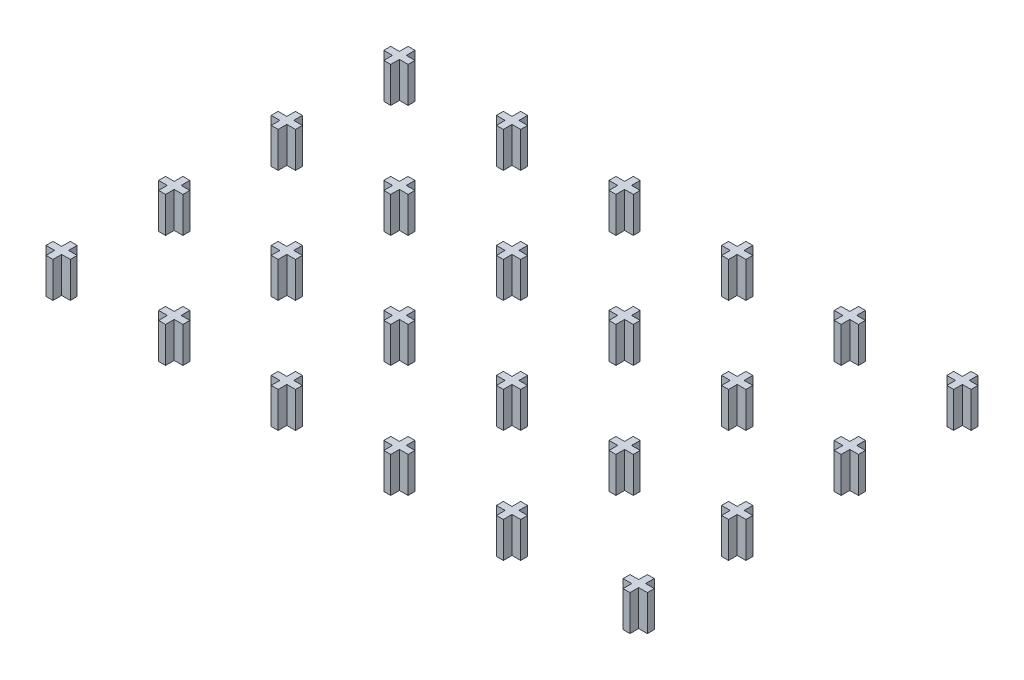
SolidWorks part; units mm, degrees
ref_plane "Front Plane" through (0, 0, 0) normal (0, 0, 1) x (1, 0, 0)
ref_plane "Top Plane" through (0, 0, 0) normal (0, 1, 0) x (1, 0, 0)
ref_plane "Right Plane" through (0, 0, 0) normal (1, 0, 0) x (0, 0, -1)
sketch "Sketch1" plane through (0, 0, 0) normal (0, 1, 0) x (1, 0, 0)
  line L0 (-32.7876, 10.5773) -> (-51.7876, 10.5773) construction
  line L1 (-51.7876, 10.5773) -> (-70.7876, 10.5773) construction
  line L2 (-51.7876, 10.5773) -> (-51.7876, 29.5773) construction
  line L3 (-51.7876, 29.5773) -> (-70.7876, 29.5773) construction
  line L4 (-70.7876, 10.5773) -> (-70.7876, 29.5773) construction
  line L5 (-51.7876, 10.5773) -> (-70.7876, 29.5773) construction
  line L6 (-51.7876, 29.5773) -> (-70.7876, 10.5773) construction
  line L7 (-32.7876, 10.5773) -> (-32.7876, 29.5773) construction
  line L8 (-32.7876, 29.5773) -> (-51.7876, 29.5773) construction
  line L9 (-51.7876, 10.5773) -> (-51.7876, 29.5773) construction
  line L10 (-32.7876, 10.5773) -> (-51.7876, 29.5773) construction
  line L11 (-32.7876, 29.5773) -> (-51.7876, 10.5773) construction
  line L12 (-13.7876, 10.5773) -> (-32.7876, 10.5773) construction
  line L13 (-13.7876, 10.5773) -> (-13.7876, 29.5773) construction
  line L14 (-13.7876, 29.5773) -> (-32.7876, 29.5773) construction
  line L15 (-32.7876, 10.5773) -> (-32.7876, 29.5773) construction
  line L16 (-13.7876, 10.5773) -> (-32.7876, 29.5773) construction
  line L17 (-13.7876, 29.5773) -> (-32.7876, 10.5773) construction
  line L18 (-32.7876, -8.4227) -> (-51.7876, -8.4227) construction
  line L19 (-51.7876, -8.4227) -> (-70.7876, -8.4227) construction
  line L20 (-51.7876, -8.4227) -> (-51.7876, 10.5773) construction
  line L21 (-51.7876, 10.5773) -> (-70.7876, 10.5773) construction
  line L22 (-70.7876, -8.4227) -> (-70.7876, 10.5773) construction
  line L23 (-51.7876, -8.4227) -> (-70.7876, 10.5773) construction
  line L24 (-51.7876, 10.5773) -> (-70.7876, -8.4227) construction
  line L25 (-32.7876, -8.4227) -> (-32.7876, 10.5773) construction
  line L26 (-32.7876, 10.5773) -> (-51.7876, 10.5773) construction
  line L27 (-51.7876, -8.4227) -> (-51.7876, 10.5773) construction
  line L28 (-32.7876, -8.4227) -> (-51.7876, 10.5773) construction
  line L29 (-32.7876, 10.5773) -> (-51.7876, -8.4227) construction
  line L30 (-13.7876, -8.4227) -> (-32.7876, -8.4227) construction
  line L31 (-13.7876, -8.4227) -> (-13.7876, 10.5773) construction
  line L32 (-13.7876, 10.5773) -> (-32.7876, 10.5773) construction
  line L33 (-32.7876, -8.4227) -> (-32.7876, 10.5773) construction
  line L34 (-13.7876, -8.4227) -> (-32.7876, 10.5773) construction
  line L35 (-13.7876, 10.5773) -> (-32.7876, -8.4227) construction
  line L36 (-32.7876, -27.4227) -> (-51.7876, -27.4227) construction
  line L37 (-51.7876, -27.4227) -> (-70.7876, -27.4227) construction
  line L38 (-51.7876, -27.4227) -> (-51.7876, -8.4227) construction
  line L39 (-51.7876, -8.4227) -> (-70.7876, -8.4227) construction
  line L40 (-70.7876, -27.4227) -> (-70.7876, -8.4227) construction
  line L41 (-51.7876, -27.4227) -> (-70.7876, -8.4227) construction
  line L42 (-51.7876, -8.4227) -> (-70.7876, -27.4227) construction
  line L43 (-32.7876, -27.4227) -> (-32.7876, -8.4227) construction
  line L44 (-32.7876, -8.4227) -> (-51.7876, -8.4227) construction
  line L45 (-51.7876, -27.4227) -> (-51.7876, -8.4227) construction
  line L46 (-32.7876, -27.4227) -> (-51.7876, -8.4227) construction
  line L47 (-32.7876, -8.4227) -> (-51.7876, -27.4227) construction
  line L48 (-13.7876, -27.4227) -> (-32.7876, -27.4227) construction
  line L49 (-13.7876, -27.4227) -> (-13.7876, -8.4227) construction
  line L50 (-13.7876, -8.4227) -> (-32.7876, -8.4227) construction
  line L51 (-32.7876, -27.4227) -> (-32.7876, -8.4227) construction
  line L52 (-13.7876, -27.4227) -> (-32.7876, -8.4227) construction
  line L53 (-13.7876, -8.4227) -> (-32.7876, -27.4227) construction
  line L54 (24.2124, 10.5773) -> (5.2124, 10.5773) construction
  line L55 (5.2124, 10.5773) -> (-13.7876, 10.5773) construction
  line L56 (5.2124, 10.5773) -> (5.2124, 29.5773) construction
  line L57 (5.2124, 29.5773) -> (-13.7876, 29.5773) construction
  line L58 (-13.7876, 10.5773) -> (-13.7876, 29.5773) construction
  line L59 (5.2124, 10.5773) -> (-13.7876, 29.5773) construction
  line L60 (5.2124, 29.5773) -> (-13.7876, 10.5773) construction
  line L61 (24.2124, 10.5773) -> (24.2124, 29.5773) construction
  line L62 (24.2124, 29.5773) -> (5.2124, 29.5773) construction
  line L63 (5.2124, 10.5773) -> (5.2124, 29.5773) construction
  line L64 (24.2124, 10.5773) -> (5.2124, 29.5773) construction
  line L65 (24.2124, 29.5773) -> (5.2124, 10.5773) construction
  line L66 (43.2124, 10.5773) -> (24.2124, 10.5773) construction
  line L67 (43.2124, 10.5773) -> (43.2124, 29.5773) construction
  line L68 (43.2124, 29.5773) -> (24.2124, 29.5773) construction
  line L69 (24.2124, 10.5773) -> (24.2124, 29.5773) construction
  line L70 (43.2124, 10.5773) -> (24.2124, 29.5773) construction
  line L71 (43.2124, 29.5773) -> (24.2124, 10.5773) construction
  line L72 (24.2124, -8.4227) -> (5.2124, -8.4227) construction
  line L73 (5.2124, -8.4227) -> (-13.7876, -8.4227) construction
  line L74 (5.2124, -8.4227) -> (5.2124, 10.5773) construction
  line L75 (5.2124, 10.5773) -> (-13.7876, 10.5773) construction
  line L76 (-13.7876, -8.4227) -> (-13.7876, 10.5773) construction
  line L77 (5.2124, -8.4227) -> (-13.7876, 10.5773) construction
  line L78 (5.2124, 10.5773) -> (-13.7876, -8.4227) construction
  line L79 (24.2124, -8.4227) -> (24.2124, 10.5773) construction
  line L80 (24.2124, 10.5773) -> (5.2124, 10.5773) construction
  line L81 (5.2124, -8.4227) -> (5.2124, 10.5773) construction
  line L82 (24.2124, -8.4227) -> (5.2124, 10.5773) construction
  line L83 (24.2124, 10.5773) -> (5.2124, -8.4227) construction
  line L84 (43.2124, -8.4227) -> (24.2124, -8.4227) construction
  line L85 (43.2124, -8.4227) -> (43.2124, 10.5773) construction
  line L86 (43.2124, 10.5773) -> (24.2124, 10.5773) construction
  line L87 (24.2124, -8.4227) -> (24.2124, 10.5773) construction
  line L88 (43.2124, -8.4227) -> (24.2124, 10.5773) construction
  line L89 (43.2124, 10.5773) -> (24.2124, -8.4227) construction
  line L90 (24.2124, -27.4227) -> (5.2124, -27.4227) construction
  line L91 (5.2124, -27.4227) -> (-13.7876, -27.4227) construction
  line L92 (5.2124, -27.4227) -> (5.2124, -8.4227) construction
  line L93 (5.2124, -8.4227) -> (-13.7876, -8.4227) construction
  line L94 (-13.7876, -27.4227) -> (-13.7876, -8.4227) construction
  line L95 (5.2124, -27.4227) -> (-13.7876, -8.4227) construction
  line L96 (5.2124, -8.4227) -> (-13.7876, -27.4227) construction
  line L97 (24.2124, -27.4227) -> (24.2124, -8.4227) construction
  line L98 (24.2124, -8.4227) -> (5.2124, -8.4227) construction
  line L99 (5.2124, -27.4227) -> (5.2124, -8.4227) construction
  line L100 (24.2124, -27.4227) -> (5.2124, -8.4227) construction
  line L101 (24.2124, -8.4227) -> (5.2124, -27.4227) construction
  line L102 (43.2124, -27.4227) -> (24.2124, -27.4227) construction
  line L103 (43.2124, -27.4227) -> (43.2124, -8.4227) construction
  line L104 (43.2124, -8.4227) -> (24.2124, -8.4227) construction
  line L105 (24.2124, -27.4227) -> (24.2124, -8.4227) construction
  line L106 (43.2124, -27.4227) -> (24.2124, -8.4227) construction
  line L107 (43.2124, -8.4227) -> (24.2124, -27.4227) construction
  line L108 (-61.8726, 22.1273) -> (-60.7026, 22.1273)
  line L109 (-60.7026, 22.1273) -> (-60.7026, 20.6623)
  line L110 (-60.7026, 20.6623) -> (-59.2376, 20.6623)
  line L111 (-59.2376, 20.6623) -> (-59.2376, 19.4923)
  line L112 (-59.2376, 19.4923) -> (-60.7026, 19.4923)
  line L113 (-60.7026, 19.4923) -> (-60.7026, 18.0273)
  line L114 (-60.7026, 18.0273) -> (-61.8726, 18.0273)
  line L115 (-61.8726, 18.0273) -> (-61.8726, 19.4923)
  line L116 (-61.8726, 19.4923) -> (-63.3376, 19.4923)
  line L117 (-63.3376, 19.4923) -> (-63.3376, 20.6623)
  line L118 (-63.3376, 20.6623) -> (-61.8726, 20.6623)
  line L119 (-61.8726, 20.6623) -> (-61.8726, 22.1273)
  line L120 (-61.8726, 20.6623) -> (-60.7026, 19.4923) construction
  line L121 (-61.8726, 19.4923) -> (-60.7026, 20.6623) construction
  line L122 (-61.8726, 3.1273) -> (-60.7026, 3.1273)
  line L123 (-60.7026, 3.1273) -> (-60.7026, 1.6623)
  line L124 (-60.7026, 1.6623) -> (-59.2376, 1.6623)
  line L125 (-59.2376, 1.6623) -> (-59.2376, 0.4923)
  line L126 (-59.2376, 0.4923) -> (-60.7026, 0.4923)
  line L127 (-60.7026, 0.4923) -> (-60.7026, -0.9727)
  line L128 (-60.7026, -0.9727) -> (-61.8726, -0.9727)
  line L129 (-61.8726, -0.9727) -> (-61.8726, 0.4923)
  line L130 (-61.8726, 0.4923) -> (-63.3376, 0.4923)
  line L131 (-63.3376, 0.4923) -> (-63.3376, 1.6623)
  line L132 (-63.3376, 1.6623) -> (-61.8726, 1.6623)
  line L133 (-61.8726, 1.6623) -> (-61.8726, 3.1273)
  line L134 (-61.8726, 1.6623) -> (-60.7026, 0.4923) construction
  line L135 (-61.8726, 0.4923) -> (-60.7026, 1.6623) construction
  line L136 (-61.8726, -15.8727) -> (-60.7026, -15.8727)
  line L137 (-60.7026, -15.8727) -> (-60.7026, -17.3377)
  line L138 (-60.7026, -17.3377) -> (-59.2376, -17.3377)
  line L139 (-59.2376, -17.3377) -> (-59.2376, -18.5077)
  line L140 (-59.2376, -18.5077) -> (-60.7026, -18.5077)
  line L141 (-60.7026, -18.5077) -> (-60.7026, -19.9727)
  line L142 (-60.7026, -19.9727) -> (-61.8726, -19.9727)
  line L143 (-61.8726, -19.9727) -> (-61.8726, -18.5077)
  line L144 (-61.8726, -18.5077) -> (-63.3376, -18.5077)
  line L145 (-63.3376, -18.5077) -> (-63.3376, -17.3377)
  line L146 (-63.3376, -17.3377) -> (-61.8726, -17.3377)
  line L147 (-61.8726, -17.3377) -> (-61.8726, -15.8727)
  line L148 (-61.8726, -17.3377) -> (-60.7026, -18.5077) construction
  line L149 (-61.8726, -18.5077) -> (-60.7026, -17.3377) construction
  line L150 (-42.8726, -15.8727) -> (-41.7026, -15.8727)
  line L151 (-41.7026, -15.8727) -> (-41.7026, -17.3377)
  line L152 (-41.7026, -17.3377) -> (-40.2376, -17.3377)
  line L153 (-40.2376, -17.3377) -> (-40.2376, -18.5077)
  line L154 (-40.2376, -18.5077) -> (-41.7026, -18.5077)
  line L155 (-41.7026, -18.5077) -> (-41.7026, -19.9727)
  line L156 (-41.7026, -19.9727) -> (-42.8726, -19.9727)
  line L157 (-42.8726, -19.9727) -> (-42.8726, -18.5077)
  line L158 (-42.8726, -18.5077) -> (-44.3376, -18.5077)
  line L159 (-44.3376, -18.5077) -> (-44.3376, -17.3377)
  line L160 (-44.3376, -17.3377) -> (-42.8726, -17.3377)
  line L161 (-42.8726, -17.3377) -> (-42.8726, -15.8727)
  line L162 (-42.8726, -17.3377) -> (-41.7026, -18.5077) construction
  line L163 (-42.8726, -18.5077) -> (-41.7026, -17.3377) construction
  line L164 (-42.8726, 3.1273) -> (-41.7026, 3.1273)
  line L165 (-41.7026, 3.1273) -> (-41.7026, 1.6623)
  line L166 (-41.7026, 1.6623) -> (-40.2376, 1.6623)
  line L167 (-40.2376, 1.6623) -> (-40.2376, 0.4923)
  line L168 (-40.2376, 0.4923) -> (-41.7026, 0.4923)
  line L169 (-41.7026, 0.4923) -> (-41.7026, -0.9727)
  line L170 (-41.7026, -0.9727) -> (-42.8726, -0.9727)
  line L171 (-42.8726, -0.9727) -> (-42.8726, 0.4923)
  line L172 (-42.8726, 0.4923) -> (-44.3376, 0.4923)
  line L173 (-44.3376, 0.4923) -> (-44.3376, 1.6623)
  line L174 (-44.3376, 1.6623) -> (-42.8726, 1.6623)
  line L175 (-42.8726, 1.6623) -> (-42.8726, 3.1273)
  line L176 (-42.8726, 1.6623) -> (-41.7026, 0.4923) construction
  line L177 (-42.8726, 0.4923) -> (-41.7026, 1.6623) construction
  line L178 (-42.8726, 22.1273) -> (-41.7026, 22.1273)
  line L179 (-41.7026, 22.1273) -> (-41.7026, 20.6623)
  line L180 (-41.7026, 20.6623) -> (-40.2376, 20.6623)
  line L181 (-40.2376, 20.6623) -> (-40.2376, 19.4923)
  line L182 (-40.2376, 19.4923) -> (-41.7026, 19.4923)
  line L183 (-41.7026, 19.4923) -> (-41.7026, 18.0273)
  line L184 (-41.7026, 18.0273) -> (-42.8726, 18.0273)
  line L185 (-42.8726, 18.0273) -> (-42.8726, 19.4923)
  line L186 (-42.8726, 19.4923) -> (-44.3376, 19.4923)
  line L187 (-44.3376, 19.4923) -> (-44.3376, 20.6623)
  line L188 (-44.3376, 20.6623) -> (-42.8726, 20.6623)
  line L189 (-42.8726, 20.6623) -> (-42.8726, 22.1273)
  line L190 (-42.8726, 20.6623) -> (-41.7026, 19.4923) construction
  line L191 (-42.8726, 19.4923) -> (-41.7026, 20.6623) construction
  line L192 (-23.8726, 22.1273) -> (-22.7026, 22.1273)
  line L193 (-22.7026, 22.1273) -> (-22.7026, 20.6623)
  line L194 (-22.7026, 20.6623) -> (-21.2376, 20.6623)
  line L195 (-21.2376, 20.6623) -> (-21.2376, 19.4923)
  line L196 (-21.2376, 19.4923) -> (-22.7026, 19.4923)
  line L197 (-22.7026, 19.4923) -> (-22.7026, 18.0273)
  line L198 (-22.7026, 18.0273) -> (-23.8726, 18.0273)
  line L199 (-23.8726, 18.0273) -> (-23.8726, 19.4923)
  line L200 (-23.8726, 19.4923) -> (-25.3376, 19.4923)
  line L201 (-25.3376, 19.4923) -> (-25.3376, 20.6623)
  line L202 (-25.3376, 20.6623) -> (-23.8726, 20.6623)
  line L203 (-23.8726, 20.6623) -> (-23.8726, 22.1273)
  line L204 (-23.8726, 20.6623) -> (-22.7026, 19.4923) construction
  line L205 (-23.8726, 19.4923) -> (-22.7026, 20.6623) construction
  line L206 (-23.8726, 3.1273) -> (-22.7026, 3.1273)
  line L207 (-22.7026, 3.1273) -> (-22.7026, 1.6623)
  line L208 (-22.7026, 1.6623) -> (-21.2376, 1.6623)
  line L209 (-21.2376, 1.6623) -> (-21.2376, 0.4923)
  line L210 (-21.2376, 0.4923) -> (-22.7026, 0.4923)
  line L211 (-22.7026, 0.4923) -> (-22.7026, -0.9727)
  line L212 (-22.7026, -0.9727) -> (-23.8726, -0.9727)
  line L213 (-23.8726, -0.9727) -> (-23.8726, 0.4923)
  line L214 (-23.8726, 0.4923) -> (-25.3376, 0.4923)
  line L215 (-25.3376, 0.4923) -> (-25.3376, 1.6623)
  line L216 (-25.3376, 1.6623) -> (-23.8726, 1.6623)
  line L217 (-23.8726, 1.6623) -> (-23.8726, 3.1273)
  line L218 (-23.8726, 1.6623) -> (-22.7026, 0.4923) construction
  line L219 (-23.8726, 0.4923) -> (-22.7026, 1.6623) construction
  line L220 (-23.8726, -15.8727) -> (-22.7026, -15.8727)
  line L221 (-22.7026, -15.8727) -> (-22.7026, -17.3377)
  line L222 (-22.7026, -17.3377) -> (-21.2376, -17.3377)
  line L223 (-21.2376, -17.3377) -> (-21.2376, -18.5077)
  line L224 (-21.2376, -18.5077) -> (-22.7026, -18.5077)
  line L225 (-22.7026, -18.5077) -> (-22.7026, -19.9727)
  line L226 (-22.7026, -19.9727) -> (-23.8726, -19.9727)
  line L227 (-23.8726, -19.9727) -> (-23.8726, -18.5077)
  line L228 (-23.8726, -18.5077) -> (-25.3376, -18.5077)
  line L229 (-25.3376, -18.5077) -> (-25.3376, -17.3377)
  line L230 (-25.3376, -17.3377) -> (-23.8726, -17.3377)
  line L231 (-23.8726, -17.3377) -> (-23.8726, -15.8727)
  line L232 (-23.8726, -17.3377) -> (-22.7026, -18.5077) construction
  line L233 (-23.8726, -18.5077) -> (-22.7026, -17.3377) construction
  line L234 (-4.8726, -15.8727) -> (-3.7026, -15.8727)
  line L235 (-3.7026, -15.8727) -> (-3.7026, -17.3377)
  line L236 (-3.7026, -17.3377) -> (-2.2376, -17.3377)
  line L237 (-2.2376, -17.3377) -> (-2.2376, -18.5077)
  line L238 (-2.2376, -18.5077) -> (-3.7026, -18.5077)
  line L239 (-3.7026, -18.5077) -> (-3.7026, -19.9727)
  line L240 (-3.7026, -19.9727) -> (-4.8726, -19.9727)
  line L241 (-4.8726, -19.9727) -> (-4.8726, -18.5077)
  line L242 (-4.8726, -18.5077) -> (-6.3376, -18.5077)
  line L243 (-6.3376, -18.5077) -> (-6.3376, -17.3377)
  line L244 (-6.3376, -17.3377) -> (-4.8726, -17.3377)
  line L245 (-4.8726, -17.3377) -> (-4.8726, -15.8727)
  line L246 (-4.8726, -17.3377) -> (-3.7026, -18.5077) construction
  line L247 (-4.8726, -18.5077) -> (-3.7026, -17.3377) construction
  line L248 (-4.8726, 3.1273) -> (-3.7026, 3.1273)
  line L249 (-3.7026, 3.1273) -> (-3.7026, 1.6623)
  line L250 (-3.7026, 1.6623) -> (-2.2376, 1.6623)
  line L251 (-2.2376, 1.6623) -> (-2.2376, 0.4923)
  line L252 (-2.2376, 0.4923) -> (-3.7026, 0.4923)
  line L253 (-3.7026, 0.4923) -> (-3.7026, -0.9727)
  line L254 (-3.7026, -0.9727) -> (-4.8726, -0.9727)
  line L255 (-4.8726, -0.9727) -> (-4.8726, 0.4923)
  line L256 (-4.8726, 0.4923) -> (-6.3376, 0.4923)
  line L257 (-6.3376, 0.4923) -> (-6.3376, 1.6623)
  line L258 (-6.3376, 1.6623) -> (-4.8726, 1.6623)
  line L259 (-4.8726, 1.6623) -> (-4.8726, 3.1273)
  line L260 (-4.8726, 1.6623) -> (-3.7026, 0.4923) construction
  line L261 (-4.8726, 0.4923) -> (-3.7026, 1.6623) construction
  line L262 (-4.8726, 22.1273) -> (-3.7026, 22.1273)
  line L263 (-3.7026, 22.1273) -> (-3.7026, 20.6623)
  line L264 (-3.7026, 20.6623) -> (-2.2376, 20.6623)
  line L265 (-2.2376, 20.6623) -> (-2.2376, 19.4923)
  line L266 (-2.2376, 19.4923) -> (-3.7026, 19.4923)
  line L267 (-3.7026, 19.4923) -> (-3.7026, 18.0273)
  line L268 (-3.7026, 18.0273) -> (-4.8726, 18.0273)
  line L269 (-4.8726, 18.0273) -> (-4.8726, 19.4923)
  line L270 (-4.8726, 19.4923) -> (-6.3376, 19.4923)
  line L271 (-6.3376, 19.4923) -> (-6.3376, 20.6623)
  line L272 (-6.3376, 20.6623) -> (-4.8726, 20.6623)
  line L273 (-4.8726, 20.6623) -> (-4.8726, 22.1273)
  line L274 (-4.8726, 20.6623) -> (-3.7026, 19.4923) construction
  line L275 (-4.8726, 19.4923) -> (-3.7026, 20.6623) construction
  line L276 (14.1274, 22.1273) -> (15.2974, 22.1273)
  line L277 (15.2974, 22.1273) -> (15.2974, 20.6623)
  line L278 (15.2974, 20.6623) -> (16.7624, 20.6623)
  line L279 (16.7624, 20.6623) -> (16.7624, 19.4923)
  line L280 (16.7624, 19.4923) -> (15.2974, 19.4923)
  line L281 (15.2974, 19.4923) -> (15.2974, 18.0273)
  line L282 (15.2974, 18.0273) -> (14.1274, 18.0273)
  line L283 (14.1274, 18.0273) -> (14.1274, 19.4923)
  line L284 (14.1274, 19.4923) -> (12.6624, 19.4923)
  line L285 (12.6624, 19.4923) -> (12.6624, 20.6623)
  line L286 (12.6624, 20.6623) -> (14.1274, 20.6623)
  line L287 (14.1274, 20.6623) -> (14.1274, 22.1273)
  line L288 (14.1274, 20.6623) -> (15.2974, 19.4923) construction
  line L289 (14.1274, 19.4923) -> (15.2974, 20.6623) construction
  line L290 (14.1274, 3.1273) -> (15.2974, 3.1273)
  line L291 (15.2974, 3.1273) -> (15.2974, 1.6623)
  line L292 (15.2974, 1.6623) -> (16.7624, 1.6623)
  line L293 (16.7624, 1.6623) -> (16.7624, 0.4923)
  line L294 (16.7624, 0.4923) -> (15.2974, 0.4923)
  line L295 (15.2974, 0.4923) -> (15.2974, -0.9727)
  line L296 (15.2974, -0.9727) -> (14.1274, -0.9727)
  line L297 (14.1274, -0.9727) -> (14.1274, 0.4923)
  line L298 (14.1274, 0.4923) -> (12.6624, 0.4923)
  line L299 (12.6624, 0.4923) -> (12.6624, 1.6623)
  line L300 (12.6624, 1.6623) -> (14.1274, 1.6623)
  line L301 (14.1274, 1.6623) -> (14.1274, 3.1273)
  line L302 (14.1274, 1.6623) -> (15.2974, 0.4923) construction
  line L303 (14.1274, 0.4923) -> (15.2974, 1.6623) construction
  line L304 (14.1274, -15.8727) -> (15.2974, -15.8727)
  line L305 (15.2974, -15.8727) -> (15.2974, -17.3377)
  line L306 (15.2974, -17.3377) -> (16.7624, -17.3377)
  line L307 (16.7624, -17.3377) -> (16.7624, -18.5077)
  line L308 (16.7624, -18.5077) -> (15.2974, -18.5077)
  line L309 (15.2974, -18.5077) -> (15.2974, -19.9727)
  line L310 (15.2974, -19.9727) -> (14.1274, -19.9727)
  line L311 (14.1274, -19.9727) -> (14.1274, -18.5077)
  line L312 (14.1274, -18.5077) -> (12.6624, -18.5077)
  line L313 (12.6624, -18.5077) -> (12.6624, -17.3377)
  line L314 (12.6624, -17.3377) -> (14.1274, -17.3377)
  line L315 (14.1274, -17.3377) -> (14.1274, -15.8727)
  line L316 (14.1274, -17.3377) -> (15.2974, -18.5077) construction
  line L317 (14.1274, -18.5077) -> (15.2974, -17.3377) construction
  line L318 (33.1274, -15.8727) -> (34.2974, -15.8727)
  line L319 (34.2974, -15.8727) -> (34.2974, -17.3377)
  line L320 (34.2974, -17.3377) -> (35.7624, -17.3377)
  line L321 (35.7624, -17.3377) -> (35.7624, -18.5077)
  line L322 (35.7624, -18.5077) -> (34.2974, -18.5077)
  line L323 (34.2974, -18.5077) -> (34.2974, -19.9727)
  line L324 (34.2974, -19.9727) -> (33.1274, -19.9727)
  line L325 (33.1274, -19.9727) -> (33.1274, -18.5077)
  line L326 (33.1274, -18.5077) -> (31.6624, -18.5077)
  line L327 (31.6624, -18.5077) -> (31.6624, -17.3377)
  line L328 (31.6624, -17.3377) -> (33.1274, -17.3377)
  line L329 (33.1274, -17.3377) -> (33.1274, -15.8727)
  line L330 (33.1274, -17.3377) -> (34.2974, -18.5077) construction
  line L331 (33.1274, -18.5077) -> (34.2974, -17.3377) construction
  line L332 (33.1274, 3.1273) -> (34.2974, 3.1273)
  line L333 (34.2974, 3.1273) -> (34.2974, 1.6623)
  line L334 (34.2974, 1.6623) -> (35.7624, 1.6623)
  line L335 (35.7624, 1.6623) -> (35.7624, 0.4923)
  line L336 (35.7624, 0.4923) -> (34.2974, 0.4923)
  line L337 (34.2974, 0.4923) -> (34.2974, -0.9727)
  line L338 (34.2974, -0.9727) -> (33.1274, -0.9727)
  line L339 (33.1274, -0.9727) -> (33.1274, 0.4923)
  line L340 (33.1274, 0.4923) -> (31.6624, 0.4923)
  line L341 (31.6624, 0.4923) -> (31.6624, 1.6623)
  line L342 (31.6624, 1.6623) -> (33.1274, 1.6623)
  line L343 (33.1274, 1.6623) -> (33.1274, 3.1273)
  line L344 (33.1274, 1.6623) -> (34.2974, 0.4923) construction
  line L345 (33.1274, 0.4923) -> (34.2974, 1.6623) construction
  line L346 (33.1274, 22.1273) -> (34.2974, 22.1273)
  line L347 (34.2974, 22.1273) -> (34.2974, 20.6623)
  line L348 (34.2974, 20.6623) -> (35.7624, 20.6623)
  line L349 (35.7624, 20.6623) -> (35.7624, 19.4923)
  line L350 (35.7624, 19.4923) -> (34.2974, 19.4923)
  line L351 (34.2974, 19.4923) -> (34.2974, 18.0273)
  line L352 (34.2974, 18.0273) -> (33.1274, 18.0273)
  line L353 (33.1274, 18.0273) -> (33.1274, 19.4923)
  line L354 (33.1274, 19.4923) -> (31.6624, 19.4923)
  line L355 (31.6624, 19.4923) -> (31.6624, 20.6623)
  line L356 (31.6624, 20.6623) -> (33.1274, 20.6623)
  line L357 (33.1274, 20.6623) -> (33.1274, 22.1273)
  line L358 (33.1274, 20.6623) -> (34.2974, 19.4923) construction
  line L359 (33.1274, 19.4923) -> (34.2974, 20.6623) construction
  line L361 (43.2124, -27.4227) -> (43.2124, -46.4227) construction
  line L362 (24.2124, -27.4227) -> (43.2124, -46.4227) construction
  line L363 (-32.7876, -46.4227) -> (-51.7876, -46.4227) construction
  line L364 (-51.7876, -46.4227) -> (-70.7876, -46.4227) construction
  line L365 (-51.7876, -46.4227) -> (-51.7876, -27.4227) construction
  line L366 (-51.7876, -27.4227) -> (-70.7876, -27.4227) construction
  line L367 (-70.7876, -46.4227) -> (-70.7876, -27.4227) construction
  line L368 (-51.7876, -46.4227) -> (-70.7876, -27.4227) construction
  line L369 (-51.7876, -27.4227) -> (-70.7876, -46.4227) construction
  line L370 (-32.7876, -46.4227) -> (-32.7876, -27.4227) construction
  line L371 (-32.7876, -27.4227) -> (-51.7876, -27.4227) construction
  line L372 (-51.7876, -46.4227) -> (-51.7876, -27.4227) construction
  line L373 (-32.7876, -46.4227) -> (-51.7876, -27.4227) construction
  line L374 (-32.7876, -27.4227) -> (-51.7876, -46.4227) construction
  line L375 (-13.7876, -46.4227) -> (-32.7876, -46.4227) construction
  line L376 (-13.7876, -46.4227) -> (-13.7876, -27.4227) construction
  line L377 (-13.7876, -27.4227) -> (-32.7876, -27.4227) construction
  line L378 (-32.7876, -46.4227) -> (-32.7876, -27.4227) construction
  line L379 (-13.7876, -46.4227) -> (-32.7876, -27.4227) construction
  line L380 (-13.7876, -27.4227) -> (-32.7876, -46.4227) construction
  line L381 (24.2124, -46.4227) -> (43.2124, -27.4227) construction
  line L382 (33.7124, -36.9227) -> (38.4624, -36.9227) construction
  line L383 (35.5024, -34.8727) -> (36.6724, -34.8727)
  line L384 (24.2124, -46.4227) -> (5.2124, -46.4227) construction
  line L385 (5.2124, -46.4227) -> (-13.7876, -46.4227) construction
  line L386 (5.2124, -46.4227) -> (5.2124, -27.4227) construction
  line L387 (5.2124, -27.4227) -> (-13.7876, -27.4227) construction
  line L388 (-13.7876, -46.4227) -> (-13.7876, -27.4227) construction
  line L389 (5.2124, -46.4227) -> (-13.7876, -27.4227) construction
  line L390 (5.2124, -27.4227) -> (-13.7876, -46.4227) construction
  line L391 (24.2124, -46.4227) -> (24.2124, -27.4227) construction
  line L392 (24.2124, -27.4227) -> (5.2124, -27.4227) construction
  line L393 (5.2124, -46.4227) -> (5.2124, -27.4227) construction
  line L394 (24.2124, -46.4227) -> (5.2124, -27.4227) construction
  line L395 (24.2124, -27.4227) -> (5.2124, -46.4227) construction
  line L396 (43.2124, -46.4227) -> (24.2124, -46.4227) construction
  line L397 (36.6724, -34.8727) -> (36.6724, -36.3377)
  line L398 (43.2124, -27.4227) -> (24.2124, -27.4227) construction
  line L399 (24.2124, -46.4227) -> (24.2124, -27.4227) construction
  line L400 (36.6724, -36.3377) -> (38.1374, -36.3377)
  line L401 (38.1374, -36.3377) -> (38.1374, -37.5077)
  line L402 (-61.8726, -34.8727) -> (-60.7026, -34.8727)
  line L403 (-60.7026, -34.8727) -> (-60.7026, -36.3377)
  line L404 (-60.7026, -36.3377) -> (-59.2376, -36.3377)
  line L405 (-59.2376, -36.3377) -> (-59.2376, -37.5077)
  line L406 (-59.2376, -37.5077) -> (-60.7026, -37.5077)
  line L407 (-60.7026, -37.5077) -> (-60.7026, -38.9727)
  line L408 (-60.7026, -38.9727) -> (-61.8726, -38.9727)
  line L409 (-61.8726, -38.9727) -> (-61.8726, -37.5077)
  line L410 (-61.8726, -37.5077) -> (-63.3376, -37.5077)
  line L411 (-63.3376, -37.5077) -> (-63.3376, -36.3377)
  line L412 (-63.3376, -36.3377) -> (-61.8726, -36.3377)
  line L413 (-61.8726, -36.3377) -> (-61.8726, -34.8727)
  line L414 (-61.8726, -36.3377) -> (-60.7026, -37.5077) construction
  line L415 (-61.8726, -37.5077) -> (-60.7026, -36.3377) construction
  line L416 (-42.8726, -34.8727) -> (-41.7026, -34.8727)
  line L417 (-41.7026, -34.8727) -> (-41.7026, -36.3377)
  line L418 (-41.7026, -36.3377) -> (-40.2376, -36.3377)
  line L419 (-40.2376, -36.3377) -> (-40.2376, -37.5077)
  line L420 (-40.2376, -37.5077) -> (-41.7026, -37.5077)
  line L421 (-41.7026, -37.5077) -> (-41.7026, -38.9727)
  line L422 (-41.7026, -38.9727) -> (-42.8726, -38.9727)
  line L423 (-42.8726, -38.9727) -> (-42.8726, -37.5077)
  line L424 (-42.8726, -37.5077) -> (-44.3376, -37.5077)
  line L425 (-44.3376, -37.5077) -> (-44.3376, -36.3377)
  line L426 (-44.3376, -36.3377) -> (-42.8726, -36.3377)
  line L427 (-42.8726, -36.3377) -> (-42.8726, -34.8727)
  line L428 (-42.8726, -36.3377) -> (-41.7026, -37.5077) construction
  line L429 (-42.8726, -37.5077) -> (-41.7026, -36.3377) construction
  line L430 (-23.8726, -34.8727) -> (-22.7026, -34.8727)
  line L431 (-22.7026, -34.8727) -> (-22.7026, -36.3377)
  line L432 (-22.7026, -36.3377) -> (-21.2376, -36.3377)
  line L433 (-21.2376, -36.3377) -> (-21.2376, -37.5077)
  line L434 (-21.2376, -37.5077) -> (-22.7026, -37.5077)
  line L435 (-22.7026, -37.5077) -> (-22.7026, -38.9727)
  line L436 (-22.7026, -38.9727) -> (-23.8726, -38.9727)
  line L437 (-23.8726, -38.9727) -> (-23.8726, -37.5077)
  line L438 (-23.8726, -37.5077) -> (-25.3376, -37.5077)
  line L439 (-25.3376, -37.5077) -> (-25.3376, -36.3377)
  line L440 (-25.3376, -36.3377) -> (-23.8726, -36.3377)
  line L441 (-23.8726, -36.3377) -> (-23.8726, -34.8727)
  line L442 (-23.8726, -36.3377) -> (-22.7026, -37.5077) construction
  line L443 (-23.8726, -37.5077) -> (-22.7026, -36.3377) construction
  line L444 (-4.8726, -34.8727) -> (-3.7026, -34.8727)
  line L445 (-3.7026, -34.8727) -> (-3.7026, -36.3377)
  line L446 (-3.7026, -36.3377) -> (-2.2376, -36.3377)
  line L447 (-2.2376, -36.3377) -> (-2.2376, -37.5077)
  line L448 (-2.2376, -37.5077) -> (-3.7026, -37.5077)
  line L449 (-3.7026, -37.5077) -> (-3.7026, -38.9727)
  line L450 (-3.7026, -38.9727) -> (-4.8726, -38.9727)
  line L451 (-4.8726, -38.9727) -> (-4.8726, -37.5077)
  line L452 (-4.8726, -37.5077) -> (-6.3376, -37.5077)
  line L453 (-6.3376, -37.5077) -> (-6.3376, -36.3377)
  line L454 (-6.3376, -36.3377) -> (-4.8726, -36.3377)
  line L455 (-4.8726, -36.3377) -> (-4.8726, -34.8727)
  line L456 (-4.8726, -36.3377) -> (-3.7026, -37.5077) construction
  line L457 (-4.8726, -37.5077) -> (-3.7026, -36.3377) construction
  line L458 (14.1274, -34.8727) -> (15.2974, -34.8727)
  line L459 (15.2974, -34.8727) -> (15.2974, -36.3377)
  line L460 (15.2974, -36.3377) -> (16.7624, -36.3377)
  line L461 (16.7624, -36.3377) -> (16.7624, -37.5077)
  line L462 (16.7624, -37.5077) -> (15.2974, -37.5077)
  line L463 (15.2974, -37.5077) -> (15.2974, -38.9727)
  line L464 (15.2974, -38.9727) -> (14.1274, -38.9727)
  line L465 (14.1274, -38.9727) -> (14.1274, -37.5077)
  line L466 (14.1274, -37.5077) -> (12.6624, -37.5077)
  line L467 (12.6624, -37.5077) -> (12.6624, -36.3377)
  line L468 (12.6624, -36.3377) -> (14.1274, -36.3377)
  line L469 (14.1274, -36.3377) -> (14.1274, -34.8727)
  line L470 (14.1274, -36.3377) -> (15.2974, -37.5077) construction
  line L471 (14.1274, -37.5077) -> (15.2974, -36.3377) construction
  line L472 (38.1374, -37.5077) -> (36.6724, -37.5077)
  line L473 (36.6724, -37.5077) -> (36.6724, -38.9727)
  line L474 (36.6724, -38.9727) -> (35.5024, -38.9727)
  line L475 (35.5024, -38.9727) -> (35.5024, -37.5077)
  line L476 (35.5024, -37.5077) -> (34.0374, -37.5077)
  line L477 (34.0374, -37.5077) -> (34.0374, -36.3377)
  line L478 (34.0374, -36.3377) -> (35.5024, -36.3377)
  line L479 (35.5024, -36.3377) -> (35.5024, -34.8727)
  line L480 (35.5024, -36.3377) -> (36.6724, -37.5077) construction
  line L481 (35.5024, -37.5077) -> (36.6724, -36.3377) construction
  line L482 (38.4624, -27.4227) -> (38.4624, -46.4227) construction
  point P0 (-61.2876, 20.0773)
  point P6 (-42.2876, 20.0773)
  point P7 (-23.2876, 20.0773)
  point P13 (-61.2876, 1.0773)
  point P18 (-61.2876, -17.9227)
  point P22 (-42.2876, 1.0773)
  point P23 (-23.2876, 1.0773)
  point P31 (-4.2876, 20.0773)
  point P35 (-42.2876, -17.9227)
  point P36 (-23.2876, -17.9227)
  point P44 (-4.2876, 1.0773)
  point P48 (14.7124, 20.0773)
  point P49 (33.7124, 20.0773)
  point P57 (-4.2876, -17.9227)
  point P61 (14.7124, 1.0773)
  point P62 (33.7124, 1.0773)
  point P75 (14.7124, -17.9227)
  point P76 (33.7124, -17.9227)
  point P289 (-61.2876, 20.0773)
  point P290 (-42.2876, 20.0773)
  point P291 (-42.2876, 1.0773)
  point P292 (-61.2876, 1.0773)
  point P293 (-61.2876, -17.9227)
  point P294 (-42.2876, -17.9227)
  point P295 (-23.2876, 20.0773)
  point P296 (-23.2876, 1.0773)
  point P297 (-23.2876, -17.9227)
  point P298 (-4.2876, -17.9227)
  point P299 (-4.2876, 1.0773)
  point P300 (-4.2876, 20.0773)
  point P301 (14.7124, 20.0773)
  point P302 (33.7124, 20.0773)
  point P303 (33.7124, 1.0773)
  point P304 (14.7124, 1.0773)
  point P305 (14.7124, -17.9227)
  point P306 (33.7124, -17.9227)
  point P307 (-61.2876, -36.9227)
  point P310 (36.0874, -36.9227)
  point P317 (-42.2876, -36.9227)
  point P318 (-23.2876, -36.9227)
  point P325 (-4.2876, -36.9227)
  point P335 (14.7124, -36.9227)
  point P336 (33.7124, -36.9227)
  point P409 (36.0874, -36.9227)
  point P415 (-61.2876, -36.9227)
  point P416 (-42.2876, -36.9227)
  point P417 (-23.2876, -36.9227)
  point P418 (-4.2876, -36.9227)
  point P419 (14.7124, -36.9227)
  dimension "D1" = 19
  dimension "D2" = 1.17
  dimension "D3" = 4.1
  dimension "D4" = 1.17
  dimension "D5" = 4.1
  dimension "D6" = 1.17
  dimension "D7" = 4.1
  dimension "D8" = 1.17
  dimension "D9" = 4.1
  dimension "D10" = 1.17
  dimension "D11" = 4.1
  dimension "D12" = 1.17
  dimension "D13" = 4.1
  dimension "D14" = 1.17
  dimension "D15" = 4.1
  dimension "D16" = 1.17
  dimension "D17" = 4.1
  dimension "D18" = 1.17
  dimension "D19" = 4.1
  dimension "D20" = 1.17
  dimension "D21" = 4.1
  dimension "D22" = 1.17
  dimension "D23" = 4.1
  dimension "D24" = 1.17
  dimension "D25" = 4.1
  dimension "D26" = 1.17
  dimension "D27" = 4.1
  dimension "D28" = 1.17
  dimension "D29" = 4.1
  dimension "D30" = 1.17
  dimension "D31" = 4.1
  dimension "D32" = 1.17
  dimension "D33" = 4.1
  dimension "D34" = 1.17
  dimension "D35" = 4.1
  dimension "D36" = 1.17
  dimension "D37" = 4.1
  dimension "D38" = 1.17
  dimension "D39" = 4.1
  dimension "D40" = 1.17
  dimension "D41" = 4.1
  dimension "D42" = 1.17
  dimension "D43" = 4.1
  dimension "D44" = 1.17
  dimension "D45" = 4.1
  dimension "D46" = 1.17
  dimension "D47" = 4.1
  dimension "D48" = 1.17
  dimension "D49" = 4.1
extrude "Boss-Extrude1" add sketch "Sketch1" along normal blind 6
